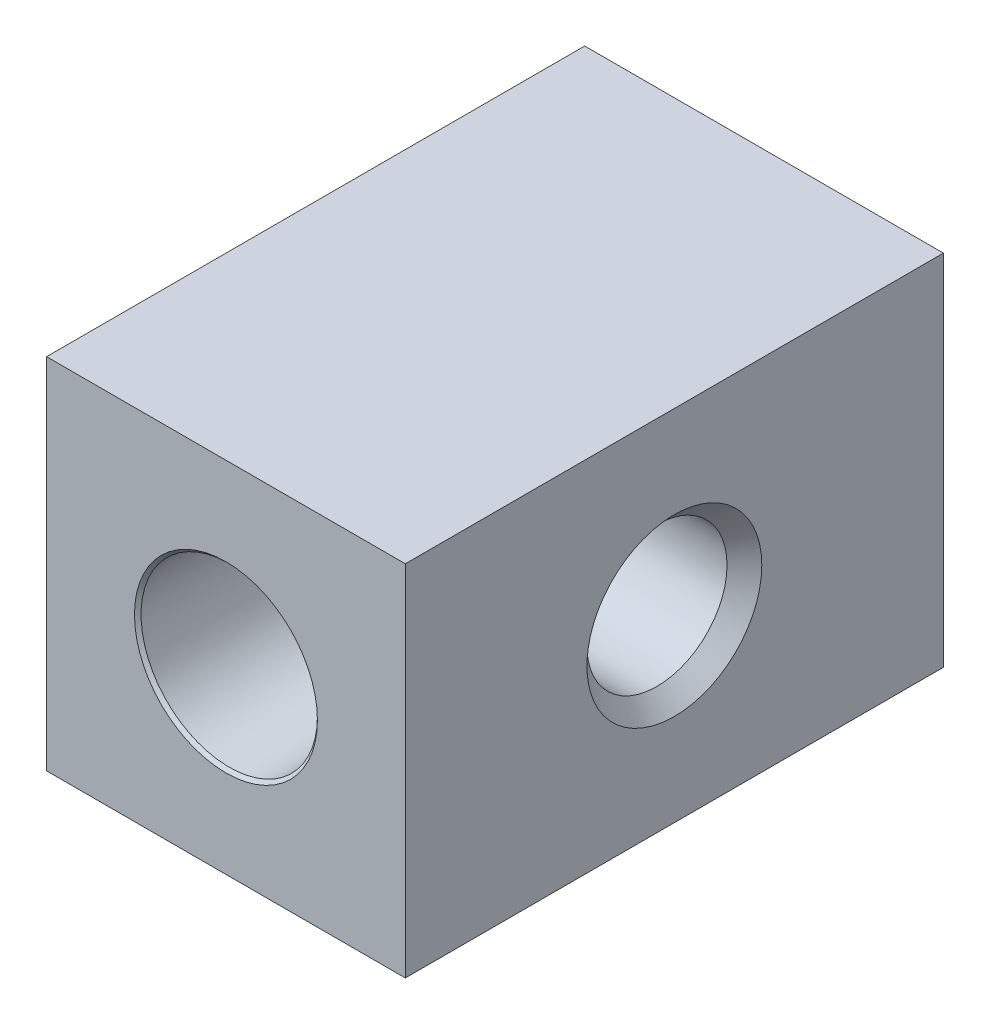
SolidWorks part; units mm, degrees
ref_plane "Front Plane" through (0, 0, 0) normal (0, 0, 1) x (1, 0, 0)
ref_plane "Top Plane" through (0, 0, 0) normal (0, 1, 0) x (1, 0, 0)
ref_plane "Right Plane" through (0, 0, 0) normal (1, 0, 0) x (0, 0, -1)
sketch "Sketch2" plane through (0, 0, 0) normal (0, 0, 1) x (1, 0, 0)
  line L1 (-12.7, 12.7) -> (12.7, 12.7)
  line L2 (-12.7, 12.7) -> (-12.7, -12.7)
  line L3 (-12.7, -12.7) -> (12.7, -12.7)
  line L4 (12.7, 12.7) -> (12.7, -12.7)
  line L5 (-12.7, 12.7) -> (12.7, -12.7) construction
  line L6 (-12.7, -12.7) -> (12.7, 12.7) construction
  point P0 (0, 0)
  dimension "D1" = 25.4
  dimension "D2" = 25.4
extrude "Boss-Extrude1" add sketch "Sketch2" along normal blind 38.1
sketch "Sketch3" plane through (0, 0, 0) normal (0, 0, -1) x (-1, 0, 0)
  circle A0 centre (0, 0) radius 5.5562
  dimension "D1" = 11.1125
sketch "Sketch4" plane through (12.7, 0, 0) normal (1, 0, 0) x (0, 0, -1)
  line L0 (0, -12.7) -> (0, 12.7) construction
  line L1 (-38.1, 12.7) -> (0, 12.7) construction
  circle A0 centre (-19.05, 0) radius 4.9609
  point P0 (-19.05, 0)
  dimension "D1" = 9.9219
  dimension "D2" = 19.05
  dimension "D3" = 12.7
hole_wizard "1/4 NPT Tapped Hole1" positions "Sketch5" profile "Sketch6" size "1/4" standard "ANSI Inch" end condition through all
sketch "Sketch5" plane through (0, 0, 38.1) normal (0, 0, 1) x (1, 0, 0)
  point P1 (0, 0)
  point P4 (0, 0)
sketch "Sketch6" plane through (0, 0, 38.1) normal (1, 0, 0) x (0, -1, 0)
  line L0 (0, 0) -> (0, 38.1)
  line L1 (0, 38.1) -> (5.5626, 38.1)
  line L3 (5.5626, 38.1) -> (5.5626, 10.02)
  line L4 (5.5626, 10.02) -> (5.9507, 10.02)
  line L5 (5.9507, 10.02) -> (6.2437, 0.2333)
  line L6 (6.2437, 0.2333) -> (6.477, 0)
  line L7 (6.477, 0) -> (0, 0)
  line L8 (0, -6.35) -> (0, 107.95) construction
  line L9 (-6.2437, 0.2333) -> (-6.477, 0) construction
  line L11 (-5.5626, 10.02) -> (-5.9507, 10.02) construction
  line L12 (-5.9507, 10.02) -> (-6.2437, 0.2333) construction
  dimension "Thru Tap Drill Dia." = 11.1252
  dimension "Thru Tap Drill Depth" = 38.1
  dimension "Thread Dia." = 12.4874
  dimension "Thread Angle" = 3.43
  dimension "Thread Depth" = 10.02
  dimension "Near C'Sink Dia." = 12.954
  dimension "Near C'Sink Angle" = 90
cosmetic thread "Hole Thread6"
cosmetic thread "Hole Thread7"
hole_wizard "1/4 NPT Tapped Hole2" positions "Sketch7" profile "Sketch8" size "1/4" standard "ANSI Inch" end condition through all
sketch "Sketch7" plane through (0, 0, 0) normal (0, 0, -1) x (-1, 0, 0)
  point P0 (0, 0)
  point P4 (0, 0)
sketch "Sketch8" plane through (0, 0, 0) normal (1, 0, 0) x (0, 1, 0)
  line L0 (0, 0) -> (0, 38.1)
  line L1 (0, 38.1) -> (5.5626, 38.1)
  line L3 (5.5626, 38.1) -> (5.5626, 10.02)
  line L4 (5.5626, 10.02) -> (5.9507, 10.02)
  line L5 (5.9507, 10.02) -> (6.2437, 0.2333)
  line L6 (6.2437, 0.2333) -> (6.477, 0)
  line L7 (6.477, 0) -> (0, 0)
  line L8 (0, -6.35) -> (0, 107.95) construction
  line L9 (-6.2437, 0.2333) -> (-6.477, 0) construction
  line L11 (-5.5626, 10.02) -> (-5.9507, 10.02) construction
  line L12 (-5.9507, 10.02) -> (-6.2437, 0.2333) construction
  dimension "Thru Tap Drill Dia." = 11.1252
  dimension "Thru Tap Drill Depth" = 38.1
  dimension "Thread Dia." = 12.4874
  dimension "Thread Angle" = 3.43
  dimension "Thread Depth" = 10.02
  dimension "Near C'Sink Dia." = 12.954
  dimension "Near C'Sink Angle" = 90
cosmetic thread "Hole Thread8"
cosmetic thread "Hole Thread9"
hole_wizard "7/16-20 Tapped Hole2" positions "Sketch4" profile "Sketch14" tap size "7/16-20" standard "ANSI Inch"
cosmetic thread "Hole Thread5"
sketch "Sketch14" plane through (12.7, 0, 19.05) normal (0, 1, 0) x (0, 0, -1)
  line L0 (0, 0) -> (0, 15.6806)
  line L1 (0, 15.6806) -> (4.9606, 12.7)
  line L2 (4.9606, 12.7) -> (4.9606, 1.2306)
  line L3 (4.9606, 1.2306) -> (6.1912, 0)
  line L5 (6.1912, 0) -> (0, 0)
  line L6 (-4.9606, 1.2306) -> (-6.1912, 0) construction
  line L10 (0, 15.6806) -> (-4.9606, 12.7) construction
  line L11 (0, -6.35) -> (0, 107.95) construction
  dimension "Tap Drill Dia." = 9.9212
  dimension "Tap Drill Depth" = 12.7
  dimension "Near C'Sink Dia." = 12.3825
  dimension "Near C'Sink Angle" = 90
  dimension "Drill Angle" = 118
